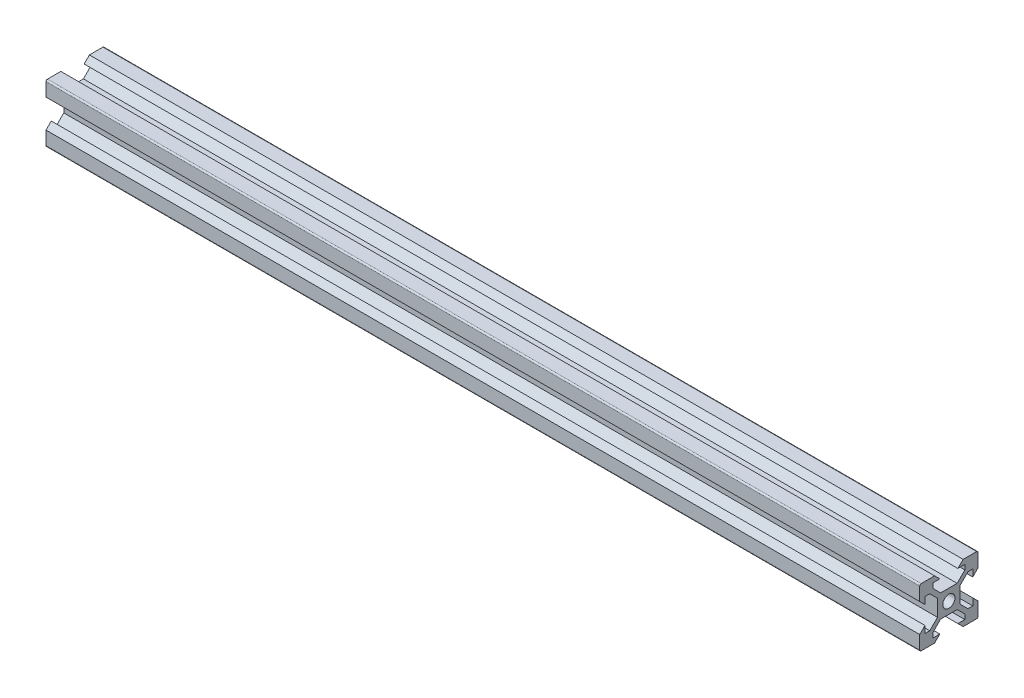
SolidWorks part; units mm, degrees
ref_plane "Alzado" through (0, 0, 0) normal (0, 0, 1) x (1, 0, 0)
ref_plane "Planta" through (0, 0, 0) normal (0, 1, 0) x (1, 0, 0)
ref_plane "Vista lateral" through (0, 0, 0) normal (1, 0, 0) x (0, 0, -1)
sketch "Croquis1" plane through (0, 0, 0) normal (1, 0, 0) x (0, 0, -1)
  line L0 (-3.9007, -2.84) -> (-6.56, -5.4993)
  line L1 (-3.9007, 3.9007) -> (3.9007, 3.9007)
  line L2 (-3.9007, 3.9007) -> (-3.9007, -3.9007)
  line L3 (-3.9007, -3.9007) -> (3.9007, -3.9007)
  line L4 (3.9007, 3.9007) -> (3.9007, -3.9007)
  line L5 (-3.9007, 3.9007) -> (3.9007, -3.9007) construction
  line L6 (-3.9007, -3.9007) -> (3.9007, 3.9007) construction
  line L7 (-2.84, -3.9007) -> (-5.4993, -6.56)
  line L8 (-5.2303, -4.1697) -> (-4.1697, -5.2303) construction
  line L9 (-6.56, -5.4993) -> (-8.2, -5.4993)
  line L10 (-8.2, -5.4993) -> (-8.2, -3.1)
  line L11 (-8.2, -3.1) -> (-10, -4.9)
  line L12 (-10, -4.9) -> (-10, -10)
  line L13 (-10, -10) -> (-4.9, -10)
  line L14 (-4.9, -10) -> (-3.1, -8.2)
  line L15 (-3.1, -8.2) -> (-5.4993, -8.2)
  line L16 (-5.4993, -8.2) -> (-5.4993, -6.56)
  line L17 (4.1697, -5.2303) -> (5.2303, -4.1697) construction
  line L18 (-3.9007, 0) -> (3.9007, 0) construction
  line L19 (5.4993, 8.2) -> (3.1, 8.2)
  line L20 (5.4993, 6.56) -> (5.4993, 8.2)
  line L21 (2.84, 3.9007) -> (5.4993, 6.56)
  line L22 (3.9007, 2.84) -> (6.56, 5.4993)
  line L23 (8.2, 5.4993) -> (6.56, 5.4993)
  line L24 (8.2, 3.1) -> (8.2, 5.4993)
  line L25 (10, 4.9) -> (8.2, 3.1)
  line L26 (10, 10) -> (10, 4.9)
  line L27 (4.9, 10) -> (10, 10)
  line L28 (3.1, 8.2) -> (4.9, 10)
  line L29 (-8.2, 5.4993) -> (-8.2, 3.1)
  line L30 (-8.2, 3.1) -> (-10, 4.9)
  line L31 (-10, 4.9) -> (-10, 10)
  line L32 (-10, 10) -> (-4.9, 10)
  line L33 (-4.9, 10) -> (-3.1, 8.2)
  line L34 (-3.1, 8.2) -> (-5.4993, 8.2)
  line L35 (-5.4993, 8.2) -> (-5.4993, 6.56)
  line L36 (-2.84, 3.9007) -> (-5.4993, 6.56)
  line L37 (2.84, -3.9007) -> (5.4993, -6.56)
  line L38 (5.4993, -6.56) -> (5.4993, -8.2)
  line L39 (5.4993, -8.2) -> (3.1, -8.2)
  line L40 (3.1, -8.2) -> (4.9, -10)
  line L41 (4.9, -10) -> (10, -10)
  line L42 (10, -10) -> (10, -4.9)
  line L43 (10, -4.9) -> (8.2, -3.1)
  line L44 (8.2, -3.1) -> (8.2, -5.4993)
  line L45 (8.2, -5.4993) -> (6.56, -5.4993)
  line L46 (3.9007, -2.84) -> (6.56, -5.4993)
  line L47 (3.9007, 2.84) -> (6.56, 5.4993) [skipped]
  line L48 (-4.9, 10) -> (-10, 10) [skipped]
  line L49 (-10, 10) -> (-10, 4.9) [skipped]
  line L50 (-10, 4.9) -> (-8.2, 3.1) [skipped]
  line L51 (-8.2, 3.1) -> (-8.2, 5.4993) [skipped]
  line L52 (-8.2, 5.4993) -> (-6.56, 5.4993) [skipped]
  line L53 (-3.9007, 2.84) -> (-6.56, 5.4993) [skipped]
  line L54 (-2.84, 3.9007) -> (-5.4993, 6.56) [skipped]
  line L55 (-5.4993, 6.56) -> (-5.4993, 8.2) [skipped]
  line L56 (-5.4993, 8.2) -> (-3.1, 8.2) [skipped]
  line L57 (-3.1, 8.2) -> (-4.9, 10) [skipped]
  line L58 (2.84, 3.9007) -> (5.4993, 6.56) [skipped]
  line L59 (5.4993, 8.2) -> (5.4993, 6.56) [skipped]
  line L60 (3.1, 8.2) -> (5.4993, 8.2) [skipped]
  line L61 (4.9, 10) -> (3.1, 8.2) [skipped]
  line L62 (10, 10) -> (4.9, 10) [skipped]
  line L63 (10, 4.9) -> (10, 10) [skipped]
  line L64 (8.2, 3.1) -> (10, 4.9) [skipped]
  line L65 (8.2, 5.4993) -> (8.2, 3.1) [skipped]
  line L66 (6.56, 5.4993) -> (8.2, 5.4993) [skipped]
  line L67 (-3.9007, 2.84) -> (-6.56, 5.4993)
  line L68 (-6.56, 5.4993) -> (-8.2, 5.4993)
  circle A0 centre (0, 0) radius 2.1
  dimension "D1" = 4.2
  dimension "D2" = 1.5
  dimension "D3" = 1.64
  dimension "D4" = 1.8
  dimension "D6" = 20
  dimension "D7" = 5.68
  dimension "D8" = 6.2
  dimension "D9" = 90
  dimension "D5" = 4
extrude "Saliente-Extruir1" add sketch "Croquis1" along normal blind 300 contours L68 L67 L2 L1 L36 L35 L34 L33 L32 L31 L30 L29 | L4 L1 L2 L3 A0 | L28 L19 L20 L21 L1 L4 L22 L23 L24 L25 L26 L27 | L46 L4 L3 L37 L38 L39 L40 L41 L42 L43 L44 L45 | L15 L16 L7 L3 L2 L0 L9 L10 L11 L12 L13 L14
fillet "Redondeo1" radius 0.5 4 edges at (150, -10, 10) (150, -10, -10) (150, 10, -10) (150, 10, 10)
